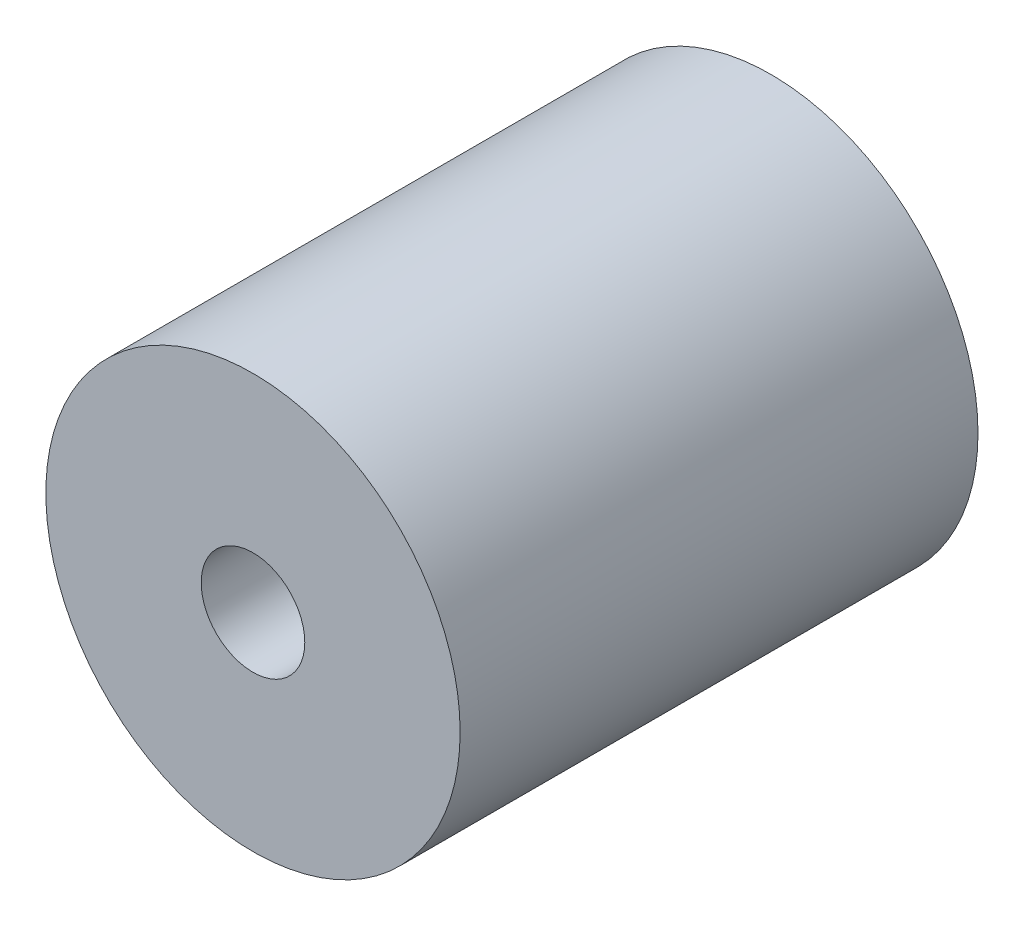
SolidWorks part; units mm, degrees
ref_plane "정면" through (0, 0, 0) normal (0, 0, 1) x (1, 0, 0)
ref_plane "윗면" through (0, 0, 0) normal (0, 1, 0) x (1, 0, 0)
ref_plane "우측면" through (0, 0, 0) normal (1, 0, 0) x (0, 0, -1)
sketch "스케치1" plane through (0, 0, 0) normal (0, 0, 1) x (1, 0, 0)
  circle A0 centre (0, 0) radius 2.5
  circle A1 centre (0, 0) radius 10
  dimension "D1" = 5
  dimension "D2" = 20
extrude "보스-돌출1" add sketch "스케치1" along normal blind 25
